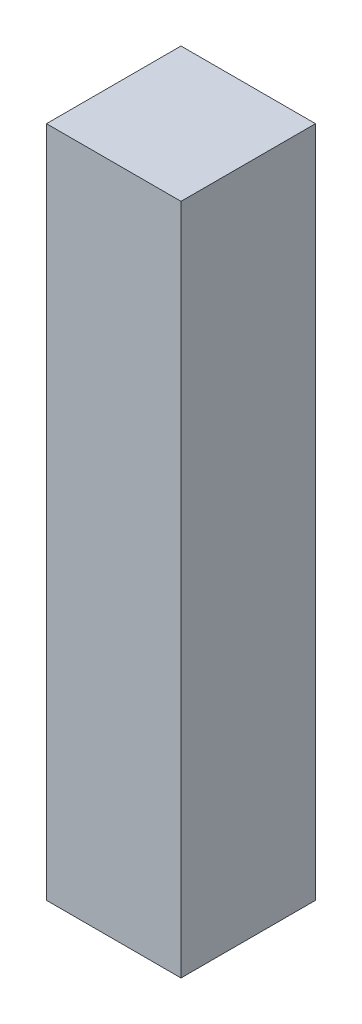
SolidWorks part; units mm, degrees
ref_plane "Front Plane" through (0, 0, 0) normal (0, 0, 1) x (1, 0, 0)
ref_plane "Top Plane" through (0, 0, 0) normal (0, 1, 0) x (1, 0, 0)
ref_plane "Right Plane" through (0, 0, 0) normal (1, 0, 0) x (0, 0, -1)
sketch "Sketch1" plane through (0, 0, 0) normal (0, 1, 0) x (1, 0, 0)
  line L1 (-4, 4) -> (4, 4)
  line L2 (-4, 4) -> (-4, -4)
  line L3 (-4, -4) -> (4, -4)
  line L4 (4, 4) -> (4, -4)
  point P4 (-4, 0)
  point P5 (0, 4)
  dimension "D1" = 8
  dimension "D2" = 8
extrude "Boss-Extrude1" add sketch "Sketch1" along normal blind 40
